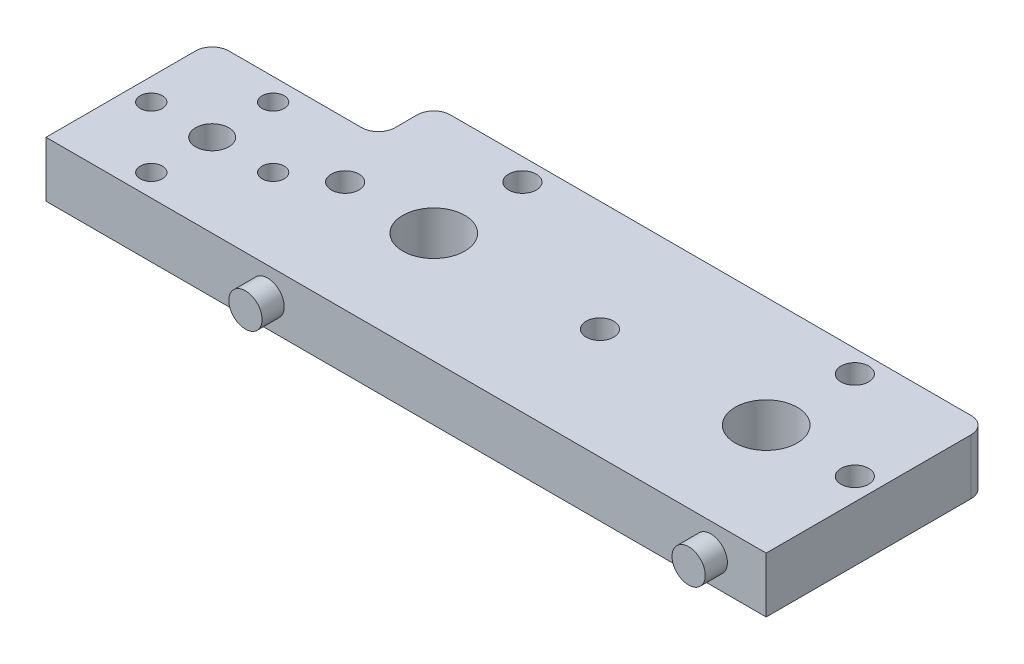
SolidWorks part; units mm, degrees
ref_plane "前视基准面" through (0, 0, 0) normal (0, 0, 1) x (1, 0, 0)
ref_plane "上视基准面" through (0, 0, 0) normal (0, 1, 0) x (1, 0, 0)
ref_plane "右视基准面" through (0, 0, 0) normal (1, 0, 0) x (0, 0, -1)
other "Configuration Table"
sketch "草图1" plane through (0, 0, 0) normal (0, 1, 0) x (1, 0, 0)
  line L0 (0, 10) -> (0, -10) construction
  line L1 (-25, 10) -> (25, 10)
  line L2 (-25, 10) -> (-25, -10)
  line L3 (-25, -10) -> (25, -10)
  line L4 (25, 10) -> (25, -10)
  line L5 (-25, 0) -> (25, 0) construction
  line L7 (-25, -10) -> (-40, -10)
  line L10 (-25, -10) -> (-25, 5)
  line L11 (-25, 5) -> (-40, 5)
  line L12 (-40, -10) -> (-40, 5)
  dimension "D1" = 50
  dimension "D2" = 20
  dimension "D6" = 15
  dimension "D7" = 15
extrude "凸台-拉伸1" add sketch "草图1" along normal blind 5 contours L2 L1 L4 L3 | L10 L7 L12 L11
sketch "草图2" plane through (0, 5, 0) normal (0, 1, 0) x (1, 0, 0)
  line L0 (0, 10) -> (0, -10) construction
  line L1 (-25, 10) -> (25, 10) construction
  line L2 (-32.5, 5) -> (-32.5, -10) construction
  line L4 (-25, 10) -> (-25, -10) construction
  line L5 (-40, -10) -> (25, -10) construction
  line L6 (-25, -10) -> (25, -10) construction
  line L7 (-25, 5) -> (-40, 5) construction
  line L8 (25, 10) -> (25, -10) construction
  line L9 (-40, -10) -> (-40, 5) construction
  line L10 (-40, -2.5) -> (-25, -2.5) construction
  circle A2 centre (0, 0) radius 1.25
  circle A3 centre (15, 0) radius 4.1
  circle A4 centre (15, 0) radius 2.8
  circle A5 centre (-15, 0) radius 4.1
  circle A6 centre (-15, 0) radius 2.8
  circle A7 centre (15, 8) radius 1.25
  circle A8 centre (23, 0) radius 1.25
  circle A9 centre (-23, 0) radius 1.25
  circle A10 centre (-15, 8) radius 1.25
  circle A11 centre (-32.5, -2.5) radius 1.5
  circle A12 centre (-27, -2.5) radius 1
  circle A13 centre (-32.5, -8) radius 1
  circle A14 centre (-38, -2.5) radius 1
  circle A15 centre (-32.5, 3) radius 1
  point P36 (0, -10)
  dimension "D3" = 2.5
  dimension "D4" = 5.6
  dimension "D5" = 8.2
  dimension "D7" = 2.5
  dimension "D8" = 2.5
  dimension "D11" = 3
  dimension "D12" = 2
  dimension "D2" = 10
  dimension "D6" = 15
  dimension "D9" = 8
  dimension "D10" = 8
  dimension "D13" = 5.5
  dimension "D14" = 4
extrude "切除-拉伸1" cut sketch "草图2" along direction (0, -1, 0) on the side against the normal up to surface (5 mm away)
fillet "圆角1" radius 1.5 4 edges at (-25, 2.5, -10) (25, 2.5, -10) (-25, 2.5, -5) (-40, 2.5, -5)
sketch "草图4" plane through (0, 0, 10) normal (0, 0, 1) x (1, 0, 0)
  line L0 (25, 2.5) -> (-40, 2.5) construction
  line L1 (25, 5) -> (25, 0) construction
  line L2 (-40, 5) -> (-40, 0) construction
  line L3 (0, 0) -> (0, 5) construction
  line L4 (-40, 5) -> (25, 5) construction
  circle A0 centre (20, 2.5) radius 1.5
  circle A1 centre (-20, 2.5) radius 1.5
  dimension "D1" = 3
  dimension "D2" = 3
  dimension "D3" = 20
  dimension "D4" = 20
extrude "凸台-拉伸2" add sketch "草图4" along normal blind 2
sketch "草图5" plane through (0, 0, -10) normal (0, 0, -1) x (-1, 0, 0)
  line L0 (-23.5, 2.5) -> (23.5, 2.5) construction
  line L1 (-23.5, 5) -> (-23.5, 0) construction
  line L2 (23.5, 0) -> (23.5, 5) construction
  line L3 (0, 5) -> (0, 0) construction
  line L4 (23.5, 5) -> (-23.5, 5) construction
  line L5 (23.5, 0) -> (-23.5, 0) construction
  circle A0 centre (-20, 2.5) radius 2
  circle A2 centre (20, 2.5) radius 2
  dimension "D1" = 4
  dimension "D3" = 20
extrude "切除-拉伸2" cut sketch "草图5" against normal blind 5
